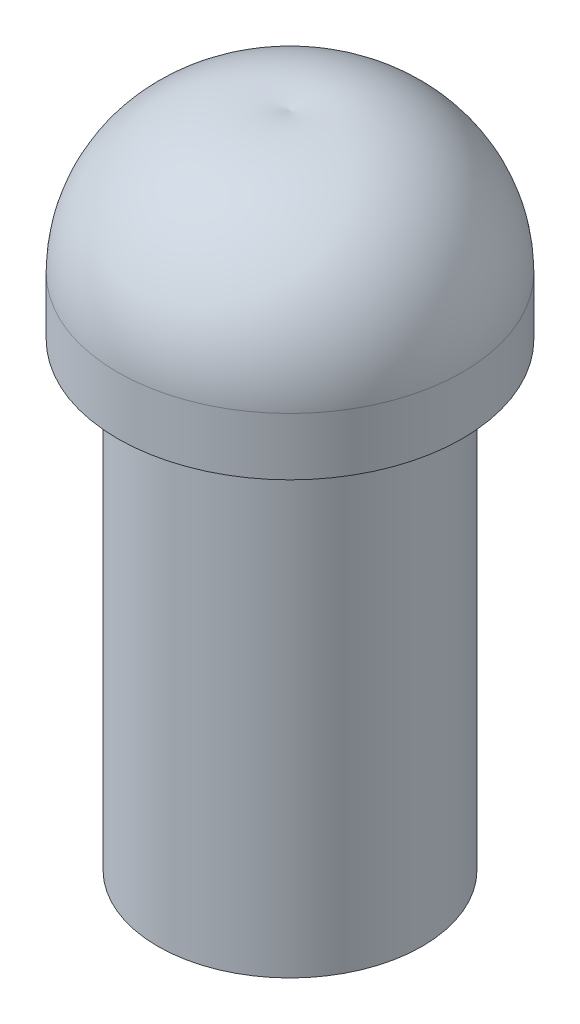
SolidWorks part; units mm, degrees
ref_plane "Přední rovina" through (0, 0, 0) normal (0, 0, 1) x (1, 0, 0)
ref_plane "Horní rovina" through (0, 0, 0) normal (0, 1, 0) x (1, 0, 0)
ref_plane "Pravá rovina" through (0, 0, 0) normal (1, 0, 0) x (0, 0, -1)
sketch "Sketch1" plane through (0, 0, 0) normal (0, 0, 1) x (1, 0, 0)
  line L0 (-2.3, 3.1121) -> (-2.3, -4.8879)
  line L1 (-2.3, -4.8879) -> (-1.55, -4.8879)
  line L2 (-1.55, -4.8879) -> (-1.55, 2.2623)
  line L3 (-1.55, 2.2623) -> (0, 2.2623)
  line L6 (-3, 4.1121) -> (-3, 3.1121)
  line L7 (-3, 3.1121) -> (-2.3, 3.1121)
  line L8 (0, 6.5616) -> (0, 2.2623)
  arc A0 (-3, 4.1121) -> (0, 6.5616) centre (-0.5, 4.1121) cw
  point P10 (-2.55, 3.1121)
  dimension "D2" = 2.5
  dimension "D1" = 8
  dimension "D3" = 1.55
  dimension "D4" = 0.75
  dimension "D5" = 1
  dimension "D6" = 3
revolve "Revolve1" add sketch "Sketch1" angle 360 about L8
